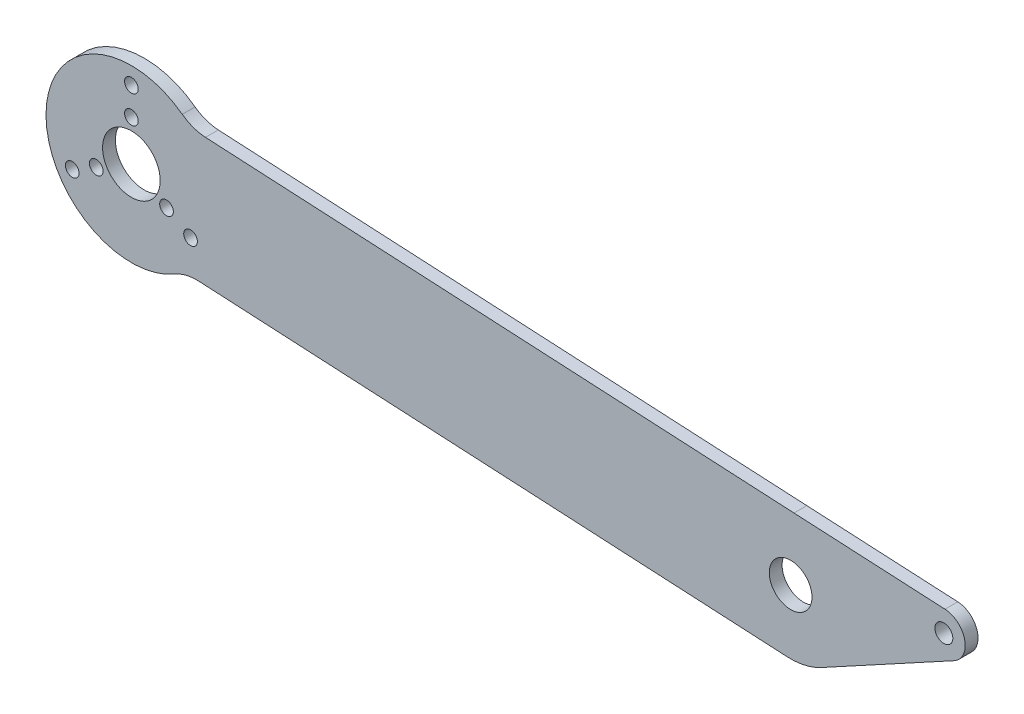
SolidWorks part; units mm, degrees
material "氧化铝"
ref_plane "前视基准面" through (0, 0, 0) normal (0, 0, 1) x (1, 0, 0)
ref_plane "上视基准面" through (0, 0, 0) normal (0, 1, 0) x (1, 0, 0)
ref_plane "右视基准面" through (0, 0, 0) normal (1, 0, 0) x (0, 0, -1)
sketch "草图1" plane through (0, 0, 0) normal (0, 0, 1) x (1, 0, 0)
  line L0 (0, 0) -> (190.28, 0) construction
  line L1 (190.28, 0) -> (154.3948, -8.1544) construction
  line L2 (154.3948, -8.1544) -> (0, 0) construction
  line L3 (12.4192, -15.6768) -> (153.6037, -23.1335)
  line L4 (161.5683, -21.3279) -> (192.6712, -4.3912)
  line L5 (14.0015, 14.2814) -> (155.1859, 6.8248)
  line L6 (190.5387, 4.9933) -> (155.1859, 6.8248)
  arc A0 (14.0015, 14.2814) -> (12.4192, -15.6768) centre (0, 0) ccw
  circle A1 centre (154.3948, -8.1544) radius 5
  circle A2 centre (190.28, 0) radius 2.1
  arc A3 (153.6037, -23.1335) -> (161.5683, -21.3279) centre (154.3948, -8.1544) ccw
  arc A4 (192.6712, -4.3912) -> (190.5387, 4.9933) centre (190.28, 0) ccw
  circle A5 centre (0, 0) radius 6.75
  circle A6 centre (0, 0) radius 9.5 construction
  circle A7 centre (0, 0) radius 16 construction
  circle A8 centre (0, 9.5) radius 1.6
  circle A9 centre (0, 16) radius 1.6
  circle A14 centre (8.2272, -4.75) radius 1.6
  circle A15 centre (0, 0) radius 9.5 construction
  circle A16 centre (-8.2272, -4.75) radius 1.6
  circle A17 centre (0, 0) radius 9.5 construction
  circle A18 centre (13.8564, -8) radius 1.6
  circle A19 centre (0, 0) radius 16 construction
  circle A20 centre (-13.8564, -8) radius 1.6
  circle A21 centre (0, 0) radius 16 construction
  point P27 (0, 0)
  point P30 (0, 0)
  point P31 (0, 0)
  point P38 (0, 0)
  dimension "D4" = 40
  dimension "D6" = 10
  dimension "D7" = 4.2
  dimension "D8" = 10
  dimension "D9" = 13.5
  dimension "D10" = 19
  dimension "D11" = 32
  dimension "D12" = 3.2
  dimension "D13" = 3.2
  dimension "D14" = 3
  dimension "D1" = 190.28
  dimension "D2" = 154.61
  dimension "D3" = 36.8
  dimension "D5" = 15
  dimension "D15" = 3
extrude "凸台-拉伸1" add sketch "草图1" along normal blind 3
fillet "圆角1" radius 10 1 edges at (14.0015, 14.2814, 1.5)
fillet "圆角2" radius 10 1 edges at (12.4192, -15.6768, 1.5)
